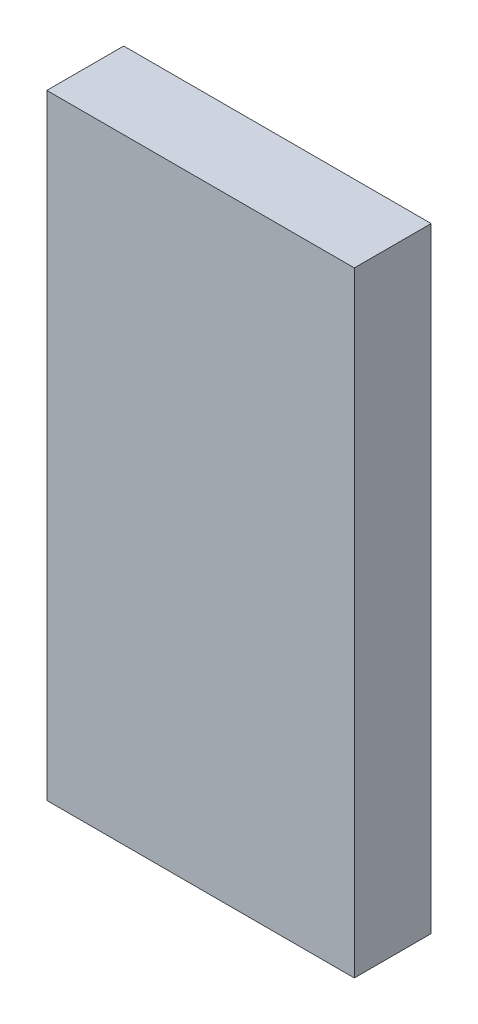
SolidWorks part; units mm, degrees
material "Glass"
ref_plane "Front Plane" through (0, 0, 0) normal (0, 0, 1) x (1, 0, 0)
ref_plane "Top Plane" through (0, 0, 0) normal (0, 1, 0) x (1, 0, 0)
ref_plane "Right Plane" through (0, 0, 0) normal (1, 0, 0) x (0, 0, -1)
sketch "Sketch1" plane through (0, 0, 0) normal (0, 0, 1) x (1, 0, 0)
  line L1 (-12.7, 25.4) -> (12.7, 25.4)
  line L2 (-12.7, 25.4) -> (-12.7, -25.4)
  line L3 (-12.7, -25.4) -> (12.7, -25.4)
  line L4 (12.7, 25.4) -> (12.7, -25.4)
  dimension "D1" = 12.7
  dimension "D2" = 12.7
  dimension "D3" = 25.4
  dimension "D4" = 25.4
extrude "Boss-Extrude1" add sketch "Sketch1" along normal mid plane 6.35
